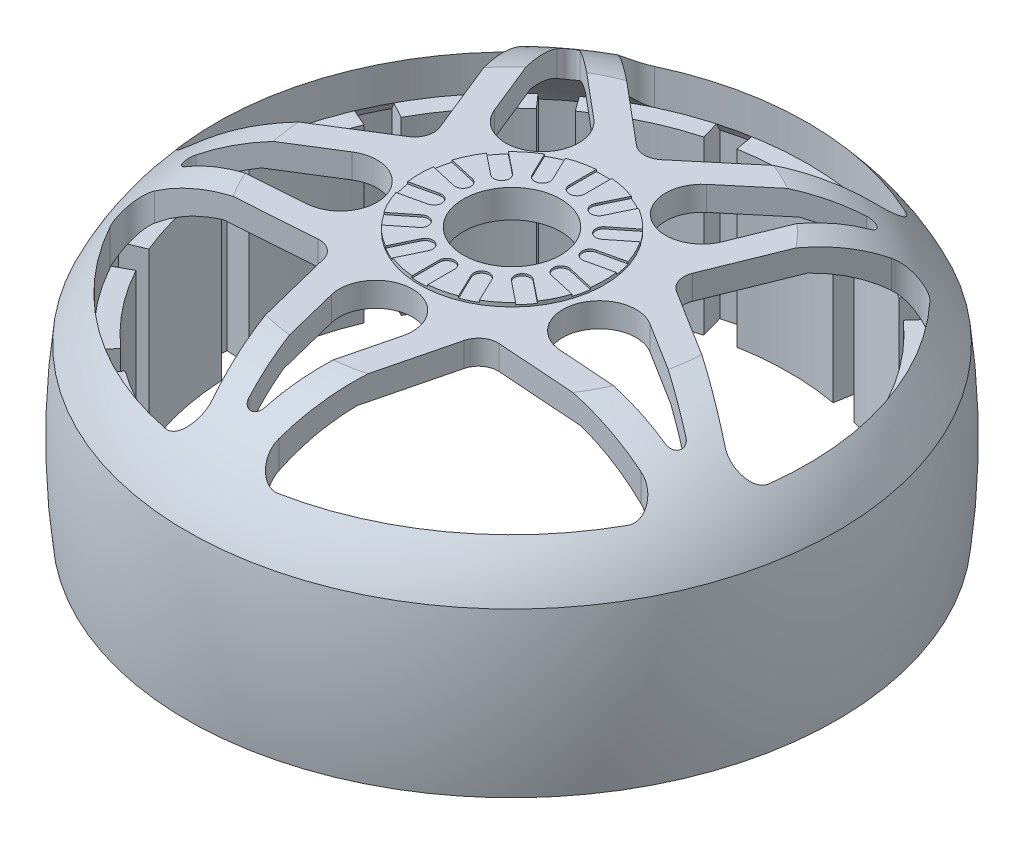
SolidWorks part; units mm, degrees
ref_plane "Front Plane" through (0, 0, 0) normal (0, 0, 1) x (1, 0, 0)
ref_plane "Top Plane" through (0, 0, 0) normal (0, 1, 0) x (1, 0, 0)
ref_plane "Right Plane" through (0, 0, 0) normal (1, 0, 0) x (0, 0, -1)
sketch "Эскиз1" plane through (0, 0, 0) normal (0, 0, 1) x (1, 0, 0)
  line L0 (0, 0) -> (0, 8.4) construction
  line L1 (18.455, 4.2) -> (-15.45, 4.2) construction
  line L2 (-16.7, 0) -> (-15.45, 0)
  line L4 (-16.7, 8.4) -> (-15.45, 8.4)
  line L5 (-15.45, 0) -> (-15.45, 8.4)
  line L6 (-16.95, 4.2) -> (-16.95, 8.4) construction
  arc A0 (-16.7, 8.4) -> (-16.7, 0) centre (18.455, 4.2) ccw
  dimension "D2" = 16.95
  dimension "D4" = 1.5
  dimension "D1" = 1.25
  dimension "D3" = 8.4
revolve "Повернуть1" add sketch "Эскиз1" angle 360 about L0
sketch "Эскиз2" plane through (0, 0, 0) normal (0, 0, 1) x (1, 0, 0)
  line L0 (0, 0) -> (0, 13.4) construction
  line L1 (-10.375, 13.4) -> (0, 13.4)
  line L2 (0, 13.4) -> (0, 12.15)
  line L3 (0, 12.15) -> (-10.7812, 12.15)
  line L4 (-15.45, 8.4) -> (-16.7, 8.4)
  arc A0 (-10.375, 13.4) -> (-16.7, 8.4) centre (-8.5474, 4.5875) ccw
  arc A1 (-10.7812, 12.15) -> (-15.45, 8.4) centre (-8.5474, 4.5875) ccw
  dimension "D3" = 9
  dimension "D1" = 13.4
  dimension "D2" = 10.375
  dimension "D4" = 1.25
revolve "Повернуть2" add sketch "Эскиз2" angle 360 about L0
sketch "Эскиз3" plane through (0, 0, 0) normal (0, 1, 0) x (1, 0, 0)
  circle A0 centre (0, 0) radius 2.5
  dimension "D1" = 5
extrude "Вырез-Вытянуть1" cut sketch "Эскиз3" along normal through all
sketch "Эскиз4" plane through (0, 0, 0) normal (0, 1, 0) x (1, 0, 0)
  line L0 (0, 0) -> (0, 16.95) construction
  line L1 (-7.8008, 13.0456) -> (0, 6.5) construction
  line L2 (7.8008, 13.0456) -> (0, 6.5) construction
  line L3 (-7.8008, 13.0456) -> (0, 6.5)
  line L4 (0, 6.5) -> (7.8008, 13.0456)
  circle A0 centre (0, 0) radius 16.95 construction
  arc A2 (7.8008, 13.0456) -> (-7.8008, 13.0456) centre (0, 0) ccw
  circle A3 centre (0, 0) radius 16.7 construction
  dimension "D3" = 1.5
  dimension "D1" = 6.5
  dimension "D2" = 100
extrude "Вырез-Вытянуть2" cut sketch "Эскиз4" along normal through all
pattern_circular "Круговой массив1" count 5 over 360 about axis through (0, 0, 0) along (0, 1, 0) of "Вырез-Вытянуть2"
sketch "Эскиз5" plane through (0, 0, 0) normal (0, 1, 0) x (1, 0, 0)
  line L0 (0, 0) -> (0, 16.7) construction
  line L1 (0, 0) -> (9.816, 13.5106) construction
  line L2 (7.362, 10.8499) -> (2.9023, 7.1078)
  line L3 (8.0439, 10.3545) -> (5.863, 4.9567)
  line L4 (8.0264, 6.574) -> (9.9966, 11.4503) construction
  line L5 (7.8008, 13.0456) -> (3.7719, 9.665) construction
  circle A0 centre (0, 0) radius 16.7 construction
  arc A1 (8.0439, 10.3545) -> (7.362, 10.8499) centre (7.6412, 10.5172) ccw
  arc A2 (2.9023, 7.1078) -> (5.863, 4.9567) centre (4.1145, 5.6631) ccw
  dimension "D1" = 36
  dimension "D2" = 7
  dimension "D3" = 1.4
  dimension "D4" = 13
extrude "Вырез-Вытянуть3" cut sketch "Эскиз5" along normal through all
pattern_circular "Круговой массив2" count 5 over 360 about axis through (0, 0, 0) along (0, 1, 0) of "Вырез-Вытянуть3"
sketch "Эскиз6" plane through (0, 0, 0) normal (0, -1, 0) x (1, 0, 0)
  line L0 (0, 0) -> (0, 15.45) construction
  line L1 (12.871, -2.6945) -> (13.8498, -2.8994) construction
  line L2 (11.1732, -6.9341) -> (12.0229, -7.4614) construction
  line L3 (0, 0) -> (2.6829, 15.2153) construction
  line L4 (0, 0) -> (-2.6829, 15.2153) construction
  line L5 (-2.6829, 15.2153) -> (-2.4745, 14.0335)
  line L6 (2.6829, 15.2153) -> (2.4745, 14.0335)
  circle A0 centre (0, 0) radius 15.45 construction
  arc A1 (2.6829, 15.2153) -> (-2.6829, 15.2153) centre (0, 0) ccw
  arc A3 (2.4745, 14.0335) -> (-2.4745, 14.0335) centre (0, 0) ccw
  point P17 (14.7749, 4.5171)
  dimension "D3" = 1.2
  dimension "D1" = 20
extrude "Бобышка-Вытянуть1" add sketch "Эскиз6" against normal up to vertex (10.0337 mm away) separate body
pattern_circular "Круговой массив5" count 14 over 360 about axis through (0, 0, 0) along (0, 1, 0) of bodies 129
fillet "Скругление1" radius 1 15 edges at (13.979, 9.7351, 5.969) (1.3571, 9.7351, 15.1393) (3.8206, 12.775, 5.2586) (9.9966, 9.7351, -11.4503) (14.8177, 9.7351, 3.3876) (6.1819, 12.775, -2.0086) (-7.8008, 9.7351, -13.0456) (7.8008, 9.7351, -13.0456) (0, 12.775, -6.5) (-9.9966, 9.7351, -11.4503) (-14.8177, 9.7351, 3.3876) (-6.1819, 12.775, -2.0086) (-13.979, 9.7351, 5.969) (-1.3571, 9.7351, 15.1393) (-3.8206, 12.775, 5.2586)
sketch "Эскиз7" plane through (0, 13.4, 0) normal (0, 1, 0) x (1, 0, 0)
  circle A0 centre (0, 0) radius 2.5 construction
  circle A1 centre (0, 0) radius 2.5
  circle A2 centre (0, 0) radius 4.75
  dimension "D1" = 9.5
extrude "Бобышка-Вытянуть2" add sketch "Эскиз7" along normal blind 0.2
sketch "Эскиз8" plane through (0, 13.6, 0) normal (0, 1, 0) x (1, 0, 0)
  line L0 (0, 0) -> (0, 4.75) construction
  line L1 (0.4, 3.35) -> (0.4, 4.7331)
  line L2 (-0.4, 3.35) -> (-0.4, 4.7331)
  circle A0 centre (0, 0) radius 4.75 construction
  arc A1 (0.4, 4.7331) -> (-0.4, 4.7331) centre (0, 0) ccw
  arc A2 (-0.4, 3.35) -> (0.4, 3.35) centre (0, 3.35) ccw
  dimension "D2" = 1.4
  dimension "D1" = 0.8
extrude "Вырез-Вытянуть4" cut sketch "Эскиз8" against normal blind 0.1
pattern_circular "Круговой массив6" count 14 over 360 about axis through (0, 0, 0) along (0, 1, 0) of "Вырез-Вытянуть4"
equation "\"D2@Эскиз2\"=20.75/2"
